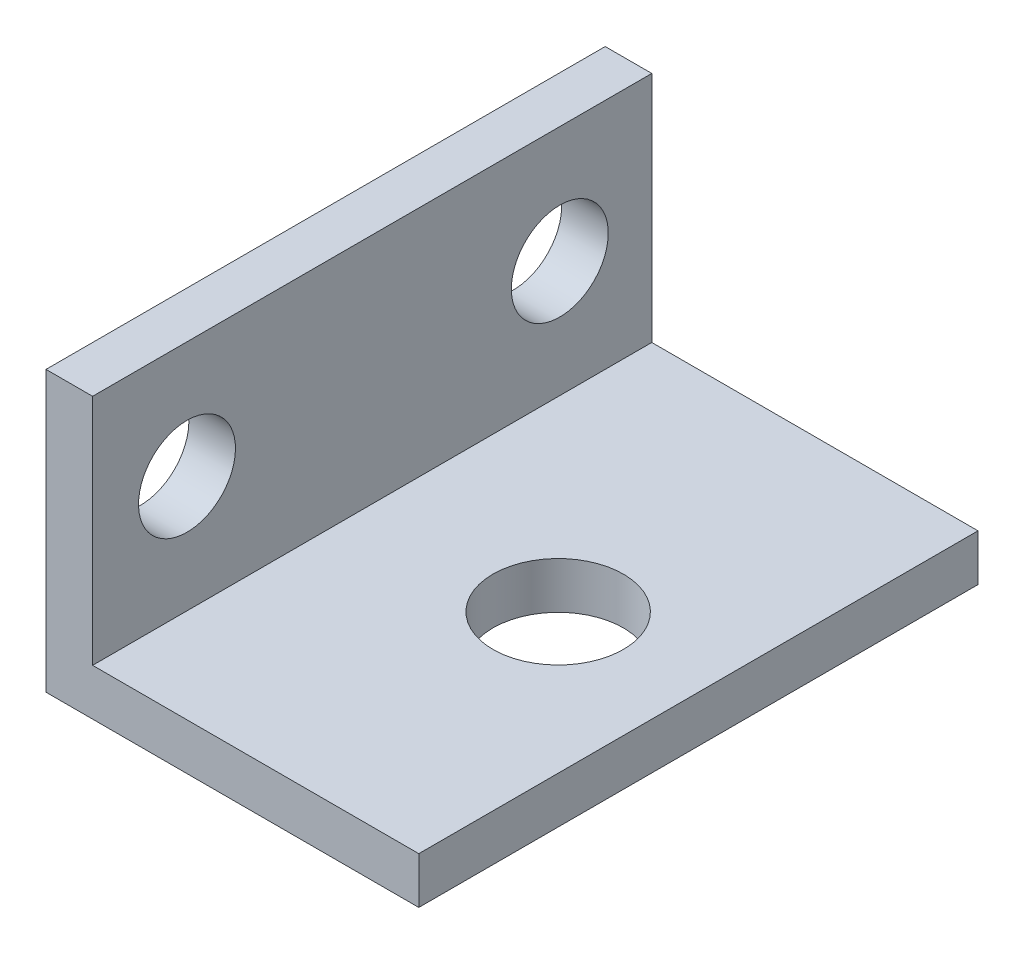
SolidWorks part; units mm, degrees
ref_plane "Front Plane" through (0, 0, 0) normal (0, 0, 1) x (1, 0, 0)
ref_plane "Top Plane" through (0, 0, 0) normal (0, 1, 0) x (1, 0, 0)
ref_plane "Right Plane" through (0, 0, 0) normal (1, 0, 0) x (0, 0, -1)
sketch "Sketch1" plane through (0, 0, 0) normal (0, 0, 1) x (1, 0, 0)
  line L0 (-5.5482, 15.875) -> (-5.5482, -3.175)
  line L1 (-5.5482, -3.175) -> (19.8518, -3.175)
  line L2 (19.8518, -3.175) -> (19.8518, 0)
  line L3 (19.8518, 0) -> (-2.3732, 0)
  line L4 (-2.3732, 0) -> (-2.3732, 15.875)
  line L5 (-2.3732, 15.875) -> (-5.5482, 15.875)
  dimension "D1" = 3.175
  dimension "D2" = 22.225
  dimension "D3" = 19.05
  dimension "D4" = 25.4
  dimension "D5" = 3.175
extrude "Boss-Extrude2" add sketch "Sketch1" along normal blind 38.1
sketch "Sketch2" plane through (0, 0, 0) normal (0, 1, 0) x (1, 0, 0)
  line L0 (19.8518, -38.1) -> (19.8518, 0) construction
  line L1 (-2.3732, -38.1) -> (-2.3732, 0) construction
  line L2 (2.7068, -15.24) -> (14.7718, -15.24) construction
  line L3 (2.7068, -15.24) -> (2.7068, -22.86) construction
  line L4 (2.7068, -22.86) -> (14.7718, -22.86) construction
  line L5 (14.7718, -15.24) -> (14.7718, -22.86) construction
  line L6 (19.8518, 0) -> (-2.3732, 0) construction
  line L7 (19.8518, -38.1) -> (-2.3732, -38.1) construction
  circle A0 centre (10.3268, -19.0786) radius 4.445
  dimension "D1" = 5.08
  dimension "D2" = 5.08
  dimension "D3" = 15.24
  dimension "D4" = 15.24
extrude "Cut-Extrude1" cut sketch "Sketch2" against normal through all both contours A0
sketch "Sketch3" plane through (-2.3732, 0, 0) normal (1, 0, 0) x (0, 0, -1)
  line L0 (-38.1, 0) -> (-38.1, 15.875) construction
  line L1 (-33.02, 12.319) -> (-23.9306, 12.319) construction
  line L2 (-33.02, 12.319) -> (-33.02, 3.556) construction
  line L3 (-33.02, 3.556) -> (-23.9306, 3.556) construction
  line L4 (-23.9306, 12.319) -> (-23.9306, 3.556) construction
  line L5 (-14.6107, 12.7) -> (-5.08, 12.7) construction
  line L6 (-14.6107, 12.7) -> (-14.6107, 3.175) construction
  line L7 (-14.6107, 3.175) -> (-5.08, 3.175) construction
  line L8 (-5.08, 12.7) -> (-5.08, 3.175) construction
  line L9 (0, 0) -> (0, 15.875) construction
  line L10 (-38.1, 15.875) -> (0, 15.875) construction
  line L11 (-38.1, 0) -> (0, 0) construction
  line L12 (-31.6693, 7.9375) -> (-6.2693, 7.9375) construction
  circle A0 centre (-6.2693, 7.9375) radius 3.302
  circle A1 centre (-31.6693, 7.9375) radius 3.302
  dimension "D7" = 6.604
  dimension "D8" = 6.604
  dimension "D11" = 6.4307
  dimension "D1" = 5.08
  dimension "D2" = 5.08
  dimension "D3" = 3.556
  dimension "D4" = 3.556
  dimension "D5" = 3.175
  dimension "D6" = 3.175
  dimension "D9" = 25.4
  dimension "D10" = 7.9375
extrude "Cut-Extrude3" cut sketch "Sketch3" against normal through all both contours A1 | A0
